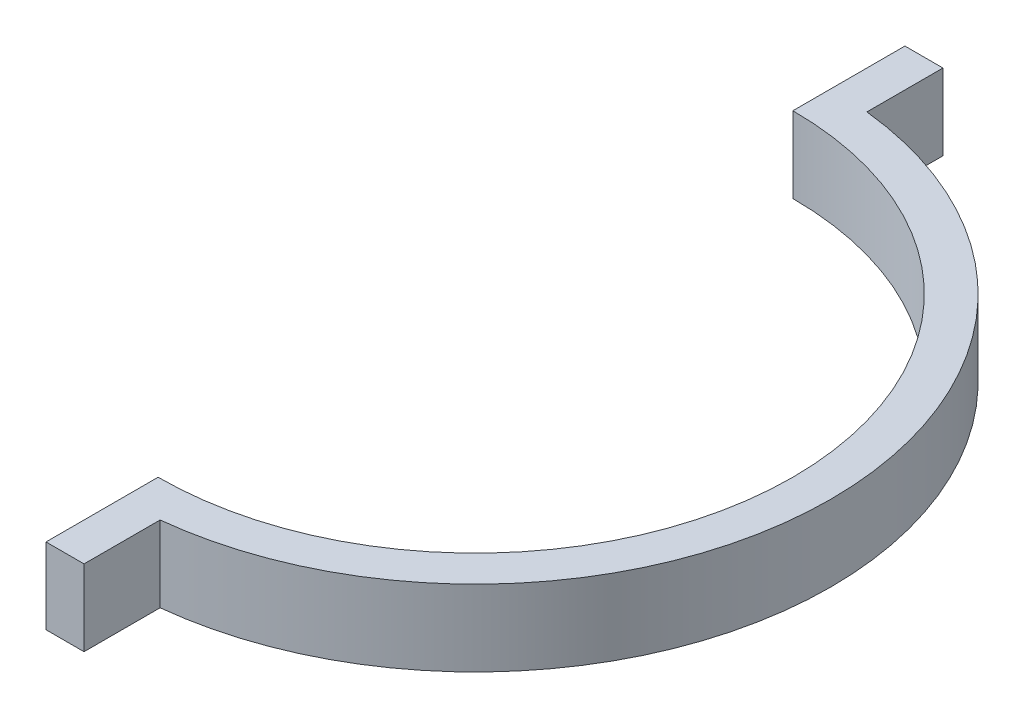
SolidWorks part; units mm, degrees
material "PBT General Purpose"
ref_plane "Front Plane" through (0, 0, 0) normal (0, 0, 1) x (1, 0, 0)
ref_plane "Top Plane" through (0, 0, 0) normal (0, 1, 0) x (1, 0, 0)
ref_plane "Right Plane" through (0, 0, 0) normal (1, 0, 0) x (0, 0, -1)
sketch "Sketch1" plane through (0, 0, 0) normal (0, 1, 0) x (1, 0, 0)
  line L0 (0, 52.9913) -> (0, 71.7006)
  line L2 (0, 71.7006) -> (6.35, 71.7006)
  line L3 (6.35, 71.7006) -> (6.35, 59.0006)
  line L4 (0, -52.9913) -> (0, -71.7006)
  line L5 (0, -71.7006) -> (6.35, -71.7006)
  line L6 (6.35, -71.7006) -> (6.35, -59.0006)
  arc A0 (0, 52.9913) -> (0, -52.9913) centre (0, 0) cw
  arc A1 (6.35, 59.0006) -> (6.35, -59.0006) centre (0, 0) cw
  dimension "D1" = 6.35
  dimension "D2" = 6.35
  dimension "D3" = 6.35
  dimension "D4" = 12.7
  dimension "D5" = 12.7
extrude "Boss-Extrude1" add sketch "Sketch1" along normal blind 12.7
